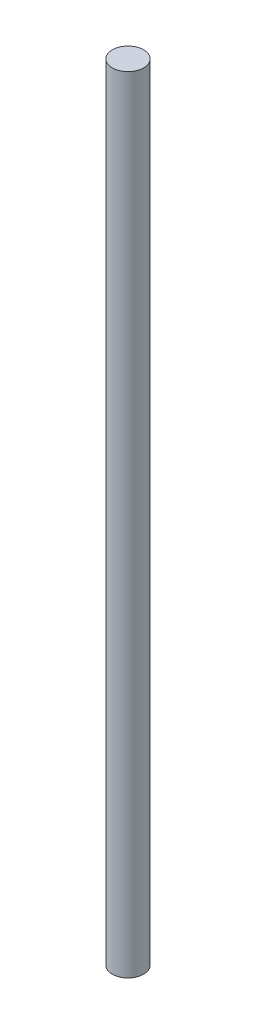
SolidWorks part; units mm, degrees
ref_plane "Front Plane" through (0, 0, 0) normal (0, 0, 1) x (1, 0, 0)
ref_plane "Top Plane" through (0, 0, 0) normal (0, 1, 0) x (1, 0, 0)
ref_plane "Right Plane" through (0, 0, 0) normal (1, 0, 0) x (0, 0, -1)
sketch "Sketch1" plane through (0, 0, 0) normal (0, 1, 0) x (1, 0, 0)
  circle A0 centre (0, 0) radius 1.5
  dimension "D1" = 3
extrude "Length" add sketch "Sketch1" along normal blind 75
